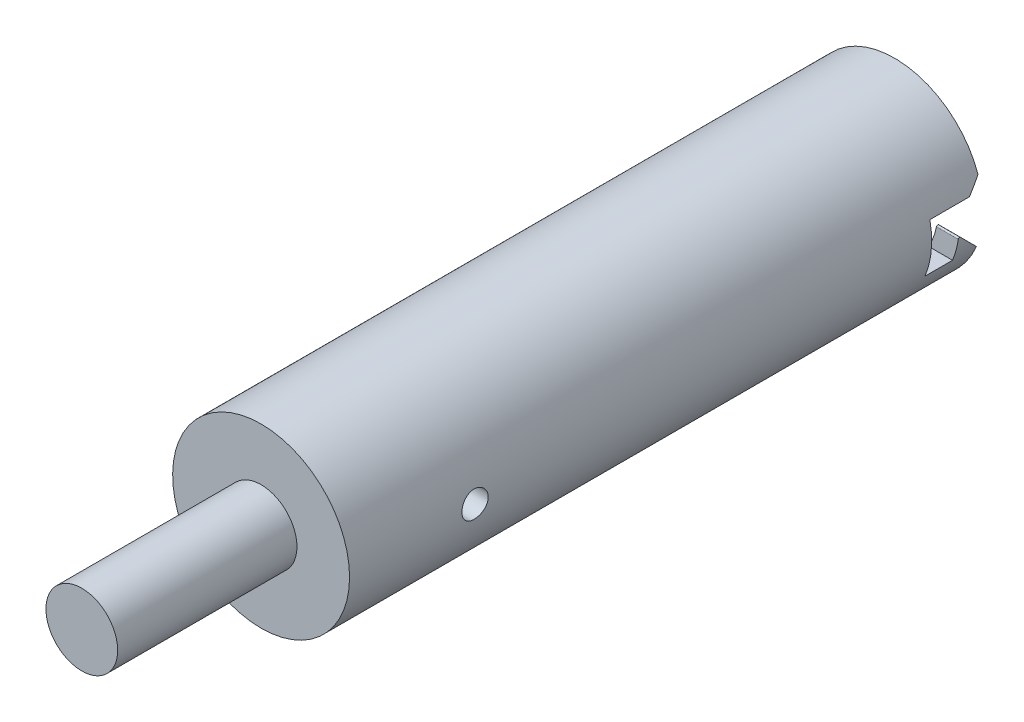
SolidWorks part; units mm, degrees
ref_plane "정면" through (0, 0, 0) normal (0, 0, 1) x (1, 0, 0)
ref_plane "윗면" through (0, 0, 0) normal (0, 1, 0) x (1, 0, 0)
ref_plane "우측면" through (0, 0, 0) normal (1, 0, 0) x (0, 0, -1)
sketch "스케치1" plane through (0, 0, 0) normal (0, 0, 1) x (1, 0, 0)
  circle A0 centre (0, 0) radius 5.6
  circle A1 centre (0, 0) radius 7.4
  dimension "D1" = 11.2
  dimension "D2" = 14.8
extrude "보스-돌출1" add sketch "스케치1" along normal blind 50
sketch "스케치2" plane through (0, 0, 0) normal (1, 0, 0) x (0, 0, -1)
  line L3 (-42.5, 0) -> (0, 0) construction
  circle A0 centre (-42.5, 0) radius 1.1
  dimension "D1" = 2.2
  dimension "D2" = 42.5
extrude "컷-돌출2" cut sketch "스케치2" against normal through all both and the other way through all
sketch "스케치3" plane through (0, 0, 50) normal (0, 0, 1) x (1, 0, 0)
  circle A0 centre (0, 0) radius 7.4
  circle A1 centre (0, 0) radius 7.4 construction
extrude "보스-돌출2" add sketch "스케치3" along normal blind 3
sketch "스케치4" plane through (0, 0, 0) normal (1, 0, 0) x (0, 0, -1)
  line L0 (-2, 0.8234) -> (-2, 2.8234)
  line L1 (0, -7.4) -> (0, 7.4) construction
  line L2 (-2, 2.8234) -> (-4.3, 2.8234)
  line L3 (-4.3, 2.8234) -> (-4.3, -1.4766)
  line L4 (-4.3, -1.4766) -> (-1, -1.4766)
  line L5 (0, -1.4766) -> (0, 2.8234)
  line L6 (-2, 2.8234) -> (0, 2.8234) construction
  line L7 (0, 2.8234) -> (-2, 0.8234)
  line L8 (-1, -1.4766) -> (0, -2.4766)
  line L9 (0, -2.4766) -> (0, -1.4766)
  line L10 (0, -1.4766) -> (-1, -1.4766) construction
  dimension "D1" = 2.3
  dimension "D2" = 45
  dimension "D3" = 2
  dimension "D4" = 2.3
  dimension "D5" = 1
  dimension "D6" = 1
extrude "컷-돌출3" cut sketch "스케치4" against normal blind 10
pattern_circular "원형 패턴1" count 2 over 360 about axis through (0, 0, 50) along (0, 0, -1) of "컷-돌출3"
sketch "스케치5" plane through (0, 0, 53) normal (0, 0, 1) x (1, 0, 0)
  circle A0 centre (0, 0) radius 3
  dimension "D1" = 6
extrude "보스-돌출3" add sketch "스케치5" along normal blind 15
chamfer "모따기2" distance 1 angle 45 1 edges at (5.6, 0, 50)
fillet "필렛1" radius 0.1 2 edges at (6.4466, -0.8234, 2) (-6.4466, 0.8234, 2)
